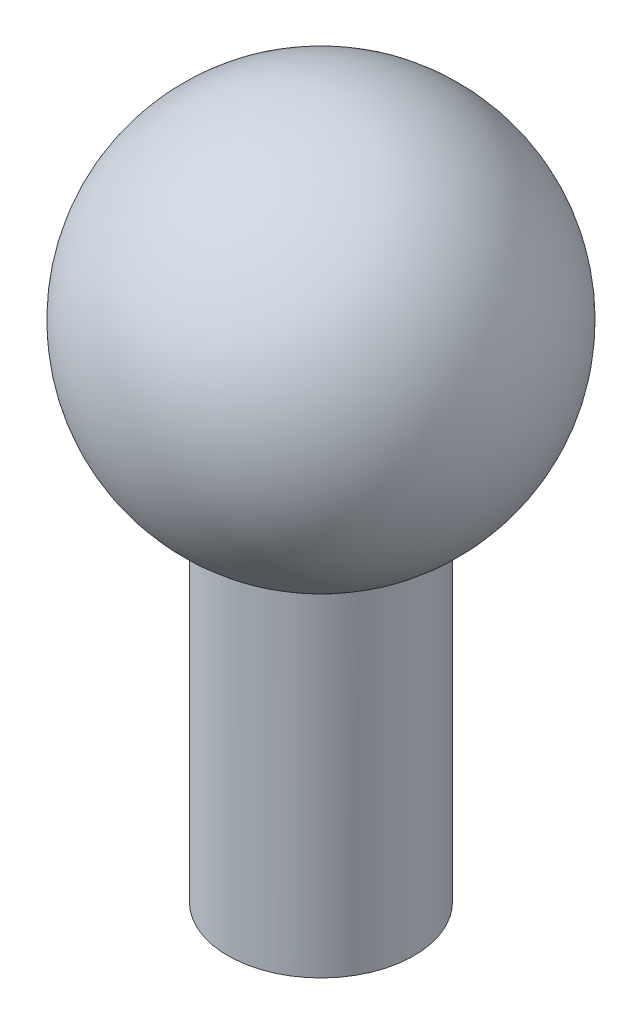
SolidWorks part; units mm, degrees
ref_plane "Front Plane" through (0, 0, 0) normal (0, 0, 1) x (1, 0, 0)
ref_plane "Top Plane" through (0, 0, 0) normal (0, 1, 0) x (1, 0, 0)
ref_plane "Right Plane" through (0, 0, 0) normal (1, 0, 0) x (0, 0, -1)
sketch "Sketch1" plane through (0, 0, 0) normal (0, 0, 1) x (1, 0, 0)
  line L0 (0, 0) -> (-12, 0)
  line L1 (-12, 0) -> (-12, 43.0683)
  line L16 (0, 0) -> (0, 90)
  arc A0 (0, 90) -> (-12, 43.0683) centre (0, 65) ccw
  dimension "D1" = 50
  dimension "D2" = 90
  dimension "D3" = 12
revolve "Revolve1" add sketch "Sketch1" angle 360 about L16
sketch "Sketch2" plane through (0, 0, 0) normal (0, -1, 0) x (-1, 0, 0)
  circle A0 centre (0, 0) radius 10
  circle A1 centre (0, -22) radius 5
  circle A2 centre (0, 22) radius 5
  dimension "D1" = 20
  dimension "D3" = 10
  dimension "D4" = 10
  dimension "D2" = 22
  dimension "D5" = 22
extrude "Cut-Extrude1" cut sketch "Sketch2" against normal blind 30
sketch "Sketch3" plane through (0, 100, 0) normal (0, 1, 0) x (1, 0, 0)
  circle A0 centre (0, 0) radius 31
  circle A1 centre (0, 0) radius 31 construction
